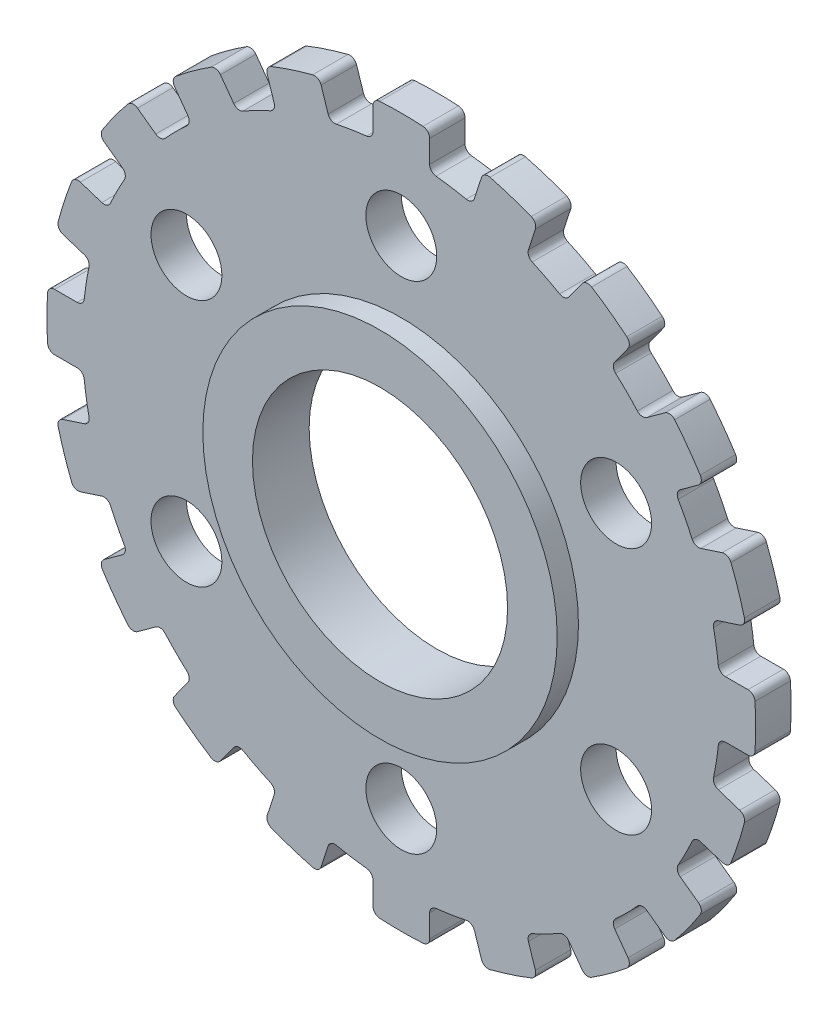
SolidWorks part; units mm, degrees
material "3.1645 (EN-AW 2030)"
ref_plane "Alzado" through (0, 0, 0) normal (0, 0, 1) x (1, 0, 0)
ref_plane "Planta" through (0, 0, 0) normal (0, 1, 0) x (1, 0, 0)
ref_plane "Vista lateral" through (0, 0, 0) normal (1, 0, 0) x (0, 0, -1)
sketch "Croquis1" plane through (0, 0, 0) normal (0, 0, 1) x (1, 0, 0)
  line L0 (11.3092, 47.7504) -> (10.3263, 44.7255)
  line L1 (-4, 47.3178) -> (4, 47.3178) construction
  line L2 (-4, 48.9081) -> (-4, 45.7275)
  line L4 (4, 48.9081) -> (4, 45.7275)
  line L5 (18.9177, 45.2783) -> (17.9348, 42.2533)
  line L6 (10.8178, 46.2379) -> (18.4262, 43.7658) construction
  line L7 (25.5114, 41.9186) -> (23.6419, 39.3454)
  line L8 (31.9835, 37.2163) -> (30.114, 34.6431)
  line L9 (24.5766, 40.632) -> (31.0488, 35.9297) construction
  line L10 (37.2163, 31.9835) -> (34.6431, 30.114)
  line L11 (41.9186, 25.5114) -> (39.3454, 23.6419)
  line L12 (35.9297, 31.0488) -> (40.632, 24.5766) construction
  line L13 (45.2783, 18.9177) -> (42.2533, 17.9348)
  line L14 (47.7504, 11.3092) -> (44.7255, 10.3263)
  line L15 (43.7658, 18.4262) -> (46.2379, 10.8178) construction
  line L16 (48.9081, 4) -> (45.7275, 4)
  line L17 (48.9081, -4) -> (45.7275, -4)
  line L18 (47.3178, 4) -> (47.3178, -4) construction
  line L19 (47.7504, -11.3092) -> (44.7255, -10.3263)
  line L20 (45.2783, -18.9177) -> (42.2533, -17.9348)
  line L21 (46.2379, -10.8178) -> (43.7658, -18.4262) construction
  line L22 (41.9186, -25.5114) -> (39.3454, -23.6419)
  line L23 (37.2163, -31.9835) -> (34.6431, -30.114)
  line L24 (40.632, -24.5766) -> (35.9297, -31.0488) construction
  line L25 (31.9835, -37.2163) -> (30.114, -34.6431)
  line L26 (25.5114, -41.9186) -> (23.6419, -39.3454)
  line L27 (31.0488, -35.9297) -> (24.5766, -40.632) construction
  line L28 (18.9177, -45.2783) -> (17.9348, -42.2533)
  line L29 (11.3092, -47.7504) -> (10.3263, -44.7255)
  line L30 (18.4262, -43.7658) -> (10.8178, -46.2379) construction
  line L31 (4, -48.9081) -> (4, -45.7275)
  line L32 (-4, -48.9081) -> (-4, -45.7275)
  line L33 (4, -47.3178) -> (-4, -47.3178) construction
  line L34 (-11.3092, -47.7504) -> (-10.3263, -44.7255)
  line L35 (-18.9177, -45.2783) -> (-17.9348, -42.2533)
  line L36 (-10.8178, -46.2379) -> (-18.4262, -43.7658) construction
  line L37 (-25.5114, -41.9186) -> (-23.6419, -39.3454)
  line L38 (-31.9835, -37.2163) -> (-30.114, -34.6431)
  line L39 (-24.5766, -40.632) -> (-31.0488, -35.9297) construction
  line L40 (-37.2163, -31.9835) -> (-34.6431, -30.114)
  line L41 (-41.9186, -25.5114) -> (-39.3454, -23.6419)
  line L42 (-35.9297, -31.0488) -> (-40.632, -24.5766) construction
  line L43 (-45.2783, -18.9177) -> (-42.2533, -17.9348)
  line L44 (-47.7504, -11.3092) -> (-44.7255, -10.3263)
  line L45 (-43.7658, -18.4262) -> (-46.2379, -10.8178) construction
  line L46 (-48.9081, -4) -> (-45.7275, -4)
  line L47 (-48.9081, 4) -> (-45.7275, 4)
  line L48 (-47.3178, -4) -> (-47.3178, 4) construction
  line L49 (-47.7504, 11.3092) -> (-44.7255, 10.3263)
  line L50 (-45.2783, 18.9177) -> (-42.2533, 17.9348)
  line L51 (-46.2379, 10.8178) -> (-43.7658, 18.4262) construction
  line L52 (-41.9186, 25.5114) -> (-39.3454, 23.6419)
  line L53 (-37.2163, 31.9835) -> (-34.6431, 30.114)
  line L54 (-40.632, 24.5766) -> (-35.9297, 31.0488) construction
  line L55 (-31.9835, 37.2163) -> (-30.114, 34.6431)
  line L56 (-25.5114, 41.9186) -> (-23.6419, 39.3454)
  line L57 (-31.0488, 35.9297) -> (-24.5766, 40.632) construction
  line L58 (-18.9177, 45.2783) -> (-17.9348, 42.2533)
  line L59 (-11.3092, 47.7504) -> (-10.3263, 44.7255)
  line L60 (-18.4262, 43.7658) -> (-10.8178, 46.2379) construction
  circle A0 centre (0, 0) radius 18
  arc A1 (-18.4753, 41.0325) -> (-22.3365, 39.0651) centre (0, 0) ccw
  arc A2 (3.0612, 49.9062) -> (-3.0612, 49.9062) centre (0, 0) ccw
  circle A3 centre (0, 35) radius 5
  circle A4 centre (30.3109, 17.5) radius 5
  circle A5 centre (30.3109, -17.5) radius 5
  circle A6 centre (0, -35) radius 5
  circle A7 centre (-30.3109, -17.5) radius 5
  circle A8 centre (-30.3109, 17.5) radius 5
  arc A9 (-4, 45.7275) -> (-4.8913, 44.7334) centre (-5, 45.7275) cw
  arc A10 (4, 45.7275) -> (4.8913, 44.7334) centre (5, 45.7275) ccw
  arc A11 (-4, 48.9081) -> (-3.0612, 49.9062) centre (-3, 48.9081) cw
  arc A12 (3.0612, 49.9062) -> (4, 48.9081) centre (3, 48.9081) cw
  arc A13 (18.3333, 46.5176) -> (12.5105, 48.4096) centre (0, 0) ccw
  arc A14 (10.3263, 44.7255) -> (9.1715, 44.0555) centre (9.3753, 45.0345) cw
  arc A15 (17.9348, 42.2533) -> (18.4753, 41.0325) centre (18.8858, 41.9443) ccw
  arc A16 (11.3092, 47.7504) -> (12.5105, 48.4096) centre (12.2603, 47.4414) cw
  arc A17 (18.3333, 46.5176) -> (18.9177, 45.2783) centre (17.9666, 45.5873) cw
  arc A18 (31.8107, 38.5756) -> (26.8575, 42.1743) centre (0, 0) ccw
  arc A19 (23.6419, 39.3454) -> (22.3365, 39.0651) centre (22.8328, 39.9332) cw
  arc A20 (30.114, 34.6431) -> (30.2508, 33.315) centre (30.923, 34.0554) ccw
  arc A21 (25.5114, 41.9186) -> (26.8575, 42.1743) centre (26.3204, 41.3308) cw
  arc A22 (31.8107, 38.5756) -> (31.9835, 37.2163) centre (31.1745, 37.8041) cw
  arc A23 (42.1743, 26.8575) -> (38.5756, 31.8107) centre (0, 0) ccw
  arc A24 (34.6431, 30.114) -> (33.315, 30.2508) centre (34.0554, 30.923) cw
  arc A25 (39.3454, 23.6419) -> (39.0651, 22.3365) centre (39.9332, 22.8328) ccw
  arc A26 (37.2163, 31.9835) -> (38.5756, 31.8107) centre (37.8041, 31.1745) cw
  arc A27 (42.1743, 26.8575) -> (41.9186, 25.5114) centre (41.3308, 26.3204) cw
  arc A28 (48.4096, 12.5105) -> (46.5176, 18.3333) centre (0, 0) ccw
  arc A29 (42.2533, 17.9348) -> (41.0325, 18.4753) centre (41.9443, 18.8858) cw
  arc A30 (44.7255, 10.3263) -> (44.0555, 9.1715) centre (45.0345, 9.3753) ccw
  arc A31 (45.2783, 18.9177) -> (46.5176, 18.3333) centre (45.5873, 17.9666) cw
  arc A32 (48.4096, 12.5105) -> (47.7504, 11.3092) centre (47.4414, 12.2603) cw
  arc A33 (49.9062, -3.0612) -> (49.9062, 3.0612) centre (0, 0) ccw
  arc A34 (45.7275, 4) -> (44.7334, 4.8913) centre (45.7275, 5) cw
  arc A35 (45.7275, -4) -> (44.7334, -4.8913) centre (45.7275, -5) ccw
  arc A36 (48.9081, 4) -> (49.9062, 3.0612) centre (48.9081, 3) cw
  arc A37 (49.9062, -3.0612) -> (48.9081, -4) centre (48.9081, -3) cw
  arc A38 (46.5176, -18.3333) -> (48.4096, -12.5105) centre (0, 0) ccw
  arc A39 (44.7255, -10.3263) -> (44.0555, -9.1715) centre (45.0345, -9.3753) cw
  arc A40 (42.2533, -17.9348) -> (41.0325, -18.4753) centre (41.9443, -18.8858) ccw
  arc A41 (47.7504, -11.3092) -> (48.4096, -12.5105) centre (47.4414, -12.2603) cw
  arc A42 (46.5176, -18.3333) -> (45.2783, -18.9177) centre (45.5873, -17.9666) cw
  arc A43 (38.5756, -31.8107) -> (42.1743, -26.8575) centre (0, 0) ccw
  arc A44 (39.3454, -23.6419) -> (39.0651, -22.3365) centre (39.9332, -22.8328) cw
  arc A45 (34.6431, -30.114) -> (33.315, -30.2508) centre (34.0554, -30.923) ccw
  arc A46 (41.9186, -25.5114) -> (42.1743, -26.8575) centre (41.3308, -26.3204) cw
  arc A47 (38.5756, -31.8107) -> (37.2163, -31.9835) centre (37.8041, -31.1745) cw
  arc A48 (26.8575, -42.1743) -> (31.8107, -38.5756) centre (0, 0) ccw
  arc A49 (30.114, -34.6431) -> (30.2508, -33.315) centre (30.923, -34.0554) cw
  arc A50 (23.6419, -39.3454) -> (22.3365, -39.0651) centre (22.8328, -39.9332) ccw
  arc A51 (31.9835, -37.2163) -> (31.8107, -38.5756) centre (31.1745, -37.8041) cw
  arc A52 (26.8575, -42.1743) -> (25.5114, -41.9186) centre (26.3204, -41.3308) cw
  arc A53 (12.5105, -48.4096) -> (18.3333, -46.5176) centre (0, 0) ccw
  arc A54 (17.9348, -42.2533) -> (18.4753, -41.0325) centre (18.8858, -41.9443) cw
  arc A55 (10.3263, -44.7255) -> (9.1715, -44.0555) centre (9.3753, -45.0345) ccw
  arc A56 (18.9177, -45.2783) -> (18.3333, -46.5176) centre (17.9666, -45.5873) cw
  arc A57 (12.5105, -48.4096) -> (11.3092, -47.7504) centre (12.2603, -47.4414) cw
  arc A58 (-3.0612, -49.9062) -> (3.0612, -49.9062) centre (0, 0) ccw
  arc A59 (4, -45.7275) -> (4.8913, -44.7334) centre (5, -45.7275) cw
  arc A60 (-4, -45.7275) -> (-4.8913, -44.7334) centre (-5, -45.7275) ccw
  arc A61 (4, -48.9081) -> (3.0612, -49.9062) centre (3, -48.9081) cw
  arc A62 (-3.0612, -49.9062) -> (-4, -48.9081) centre (-3, -48.9081) cw
  arc A63 (-18.3333, -46.5176) -> (-12.5105, -48.4096) centre (0, 0) ccw
  arc A64 (-10.3263, -44.7255) -> (-9.1715, -44.0555) centre (-9.3753, -45.0345) cw
  arc A65 (-17.9348, -42.2533) -> (-18.4753, -41.0325) centre (-18.8858, -41.9443) ccw
  arc A66 (-11.3092, -47.7504) -> (-12.5105, -48.4096) centre (-12.2603, -47.4414) cw
  arc A67 (-18.3333, -46.5176) -> (-18.9177, -45.2783) centre (-17.9666, -45.5873) cw
  arc A68 (-31.8107, -38.5756) -> (-26.8575, -42.1743) centre (0, 0) ccw
  arc A69 (-23.6419, -39.3454) -> (-22.3365, -39.0651) centre (-22.8328, -39.9332) cw
  arc A70 (-30.114, -34.6431) -> (-30.2508, -33.315) centre (-30.923, -34.0554) ccw
  arc A71 (-25.5114, -41.9186) -> (-26.8575, -42.1743) centre (-26.3204, -41.3308) cw
  arc A72 (-31.8107, -38.5756) -> (-31.9835, -37.2163) centre (-31.1745, -37.8041) cw
  arc A73 (-42.1743, -26.8575) -> (-38.5756, -31.8107) centre (0, 0) ccw
  arc A74 (-34.6431, -30.114) -> (-33.315, -30.2508) centre (-34.0554, -30.923) cw
  arc A75 (-39.3454, -23.6419) -> (-39.0651, -22.3365) centre (-39.9332, -22.8328) ccw
  arc A76 (-37.2163, -31.9835) -> (-38.5756, -31.8107) centre (-37.8041, -31.1745) cw
  arc A77 (-42.1743, -26.8575) -> (-41.9186, -25.5114) centre (-41.3308, -26.3204) cw
  arc A78 (-48.4096, -12.5105) -> (-46.5176, -18.3333) centre (0, 0) ccw
  arc A79 (-42.2533, -17.9348) -> (-41.0325, -18.4753) centre (-41.9443, -18.8858) cw
  arc A80 (-44.7255, -10.3263) -> (-44.0555, -9.1715) centre (-45.0345, -9.3753) ccw
  arc A81 (-45.2783, -18.9177) -> (-46.5176, -18.3333) centre (-45.5873, -17.9666) cw
  arc A82 (-48.4096, -12.5105) -> (-47.7504, -11.3092) centre (-47.4414, -12.2603) cw
  arc A83 (-49.9062, 3.0612) -> (-49.9062, -3.0612) centre (0, 0) ccw
  arc A84 (-45.7275, -4) -> (-44.7334, -4.8913) centre (-45.7275, -5) cw
  arc A85 (-45.7275, 4) -> (-44.7334, 4.8913) centre (-45.7275, 5) ccw
  arc A86 (-48.9081, -4) -> (-49.9062, -3.0612) centre (-48.9081, -3) cw
  arc A87 (-49.9062, 3.0612) -> (-48.9081, 4) centre (-48.9081, 3) cw
  arc A88 (-46.5176, 18.3333) -> (-48.4096, 12.5105) centre (0, 0) ccw
  arc A89 (-44.7255, 10.3263) -> (-44.0555, 9.1715) centre (-45.0345, 9.3753) cw
  arc A90 (-42.2533, 17.9348) -> (-41.0325, 18.4753) centre (-41.9443, 18.8858) ccw
  arc A91 (-47.7504, 11.3092) -> (-48.4096, 12.5105) centre (-47.4414, 12.2603) cw
  arc A92 (-46.5176, 18.3333) -> (-45.2783, 18.9177) centre (-45.5873, 17.9666) cw
  arc A93 (-38.5756, 31.8107) -> (-42.1743, 26.8575) centre (0, 0) ccw
  arc A94 (-39.3454, 23.6419) -> (-39.0651, 22.3365) centre (-39.9332, 22.8328) cw
  arc A95 (-34.6431, 30.114) -> (-33.315, 30.2508) centre (-34.0554, 30.923) ccw
  arc A96 (-41.9186, 25.5114) -> (-42.1743, 26.8575) centre (-41.3308, 26.3204) cw
  arc A97 (-38.5756, 31.8107) -> (-37.2163, 31.9835) centre (-37.8041, 31.1745) cw
  arc A98 (-26.8575, 42.1743) -> (-31.8107, 38.5756) centre (0, 0) ccw
  arc A99 (-30.114, 34.6431) -> (-30.2508, 33.315) centre (-30.923, 34.0554) cw
  arc A100 (-23.6419, 39.3454) -> (-22.3365, 39.0651) centre (-22.8328, 39.9332) ccw
  arc A101 (-31.9835, 37.2163) -> (-31.8107, 38.5756) centre (-31.1745, 37.8041) cw
  arc A102 (-26.8575, 42.1743) -> (-25.5114, 41.9186) centre (-26.3204, 41.3308) cw
  arc A103 (-12.5105, 48.4096) -> (-18.3333, 46.5176) centre (0, 0) ccw
  arc A104 (-17.9348, 42.2533) -> (-18.4753, 41.0325) centre (-18.8858, 41.9443) cw
  arc A105 (-10.3263, 44.7255) -> (-9.1715, 44.0555) centre (-9.3753, 45.0345) ccw
  arc A106 (-18.9177, 45.2783) -> (-18.3333, 46.5176) centre (-17.9666, 45.5873) cw
  arc A107 (-12.5105, 48.4096) -> (-11.3092, 47.7504) centre (-12.2603, 47.4414) cw
  arc A108 (-4.8913, 44.7334) -> (-9.1715, 44.0555) centre (0, 0) ccw
  arc A109 (9.1715, 44.0555) -> (4.8913, 44.7334) centre (0, 0) ccw
  arc A110 (22.3365, 39.0651) -> (18.4753, 41.0325) centre (0, 0) ccw
  arc A111 (41.0325, 18.4753) -> (39.0651, 22.3365) centre (0, 0) ccw
  arc A112 (33.315, 30.2508) -> (30.2508, 33.315) centre (0, 0) ccw
  arc A113 (44.7334, 4.8913) -> (44.0555, 9.1715) centre (0, 0) ccw
  arc A114 (44.0555, -9.1715) -> (44.7334, -4.8913) centre (0, 0) ccw
  arc A115 (39.0651, -22.3365) -> (41.0325, -18.4753) centre (0, 0) ccw
  arc A116 (30.2508, -33.315) -> (33.315, -30.2508) centre (0, 0) ccw
  arc A117 (18.4753, -41.0325) -> (22.3365, -39.0651) centre (0, 0) ccw
  arc A118 (4.8913, -44.7334) -> (9.1715, -44.0555) centre (0, 0) ccw
  arc A119 (-22.3365, -39.0651) -> (-18.4753, -41.0325) centre (0, 0) ccw
  arc A120 (-33.315, -30.2508) -> (-30.2508, -33.315) centre (0, 0) ccw
  arc A121 (-9.1715, -44.0555) -> (-4.8913, -44.7334) centre (0, 0) ccw
  arc A122 (-41.0325, -18.4753) -> (-39.0651, -22.3365) centre (0, 0) ccw
  arc A123 (-44.7334, -4.8913) -> (-44.0555, -9.1715) centre (0, 0) ccw
  arc A124 (-44.0555, 9.1715) -> (-44.7334, 4.8913) centre (0, 0) ccw
  arc A125 (-39.0651, 22.3365) -> (-41.0325, 18.4753) centre (0, 0) ccw
  arc A126 (-30.2508, 33.315) -> (-33.315, 30.2508) centre (0, 0) ccw
  point P9 (0, 47.3178)
  point P19 (0, 0)
  point P301 (0, 0)
  point P303 (-4, 47.3178)
  dimension "D1" = 36
  dimension "D2" = 90
  dimension "D3" = 100
  dimension "D4" = 10
  dimension "D7" = 35
  dimension "D9" = 1
  dimension "D10" = 8
  dimension "D8" = 1
  dimension "D11" = 1
  dimension "D12" = 1
  dimension "D5" = 35
  dimension "D6" = 6
  dimension "D13" = 20
extrude "Saliente-Extruir1" add sketch "Croquis1" along normal blind 5
sketch "Croquis2" plane through (0, 0, 5) normal (0, 0, 1) x (1, 0, 0)
  circle A0 centre (0, 0) radius 25
  circle A1 centre (0, 0) radius 18 construction
  circle A2 centre (0, 0) radius 18
  dimension "D1" = 50
extrude "Saliente-Extruir2" add sketch "Croquis2" along normal blind 3 contours A2 | A0
